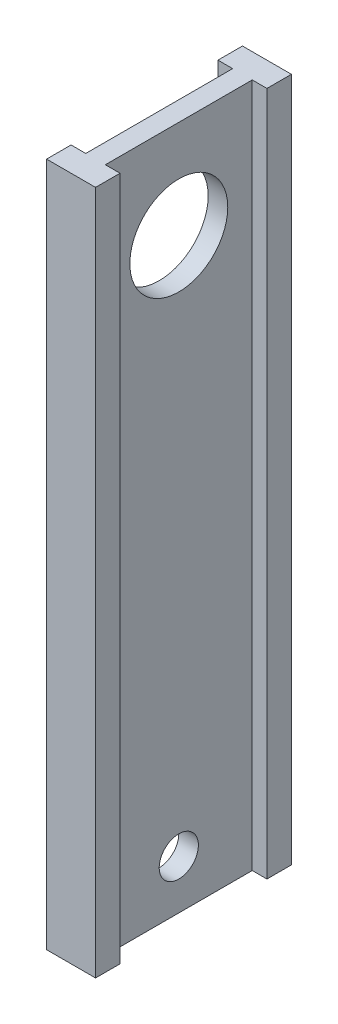
SolidWorks part; units mm, degrees
material "PE High Density"
ref_plane "Front Plane" through (0, 0, 0) normal (0, 0, 1) x (1, 0, 0)
ref_plane "Top Plane" through (0, 0, 0) normal (0, 1, 0) x (1, 0, 0)
ref_plane "Right Plane" through (0, 0, 0) normal (1, 0, 0) x (0, 0, -1)
sketch "Sketch1" plane through (0, 0, 0) normal (0, 1, 0) x (1, 0, 0)
  line L0 (-25, -75) -> (-25, -100)
  line L1 (-25, 100) -> (25, 100)
  line L2 (-25, 100) -> (-25, 75)
  line L3 (-25, -100) -> (25, -100)
  line L4 (25, 100) -> (25, 75)
  line L7 (-25, 75) -> (-10, 75)
  line L9 (-25, -75) -> (-10, -75)
  line L10 (-10, 75) -> (-10, -75)
  line L11 (25, 75) -> (10, 75)
  line L13 (25, -75) -> (10, -75)
  line L14 (10, 75) -> (10, -75)
  line L15 (25, -75) -> (25, -100)
  point P0 (0, 0)
  dimension "D1" = 50
  dimension "D2" = 200
  dimension "D3" = 150
  dimension "D4" = 25
  dimension "D5" = 15
  dimension "D6" = 20
extrude "Boss-Extrude1" add sketch "Sketch1" along normal blind 699.1067
sketch "Sketch2" plane through (10, 0, 0) normal (1, 0, 0) x (0, 0, -1)
  line L0 (-75, 699.1067) -> (75, 699.1067) construction
  line L1 (-75, 0) -> (75, 0) construction
  circle A0 centre (0, 599.1067) radius 50
  circle A1 centre (0, 50) radius 20
  dimension "D1" = 100
  dimension "D3" = 40
  dimension "D2" = 100
  dimension "D4" = 50
extrude "Cut-Extrude1" cut sketch "Sketch2" against normal blind 1000
scale "Scale1" scale about centroid uniform scaling yes scale factor 0.75
